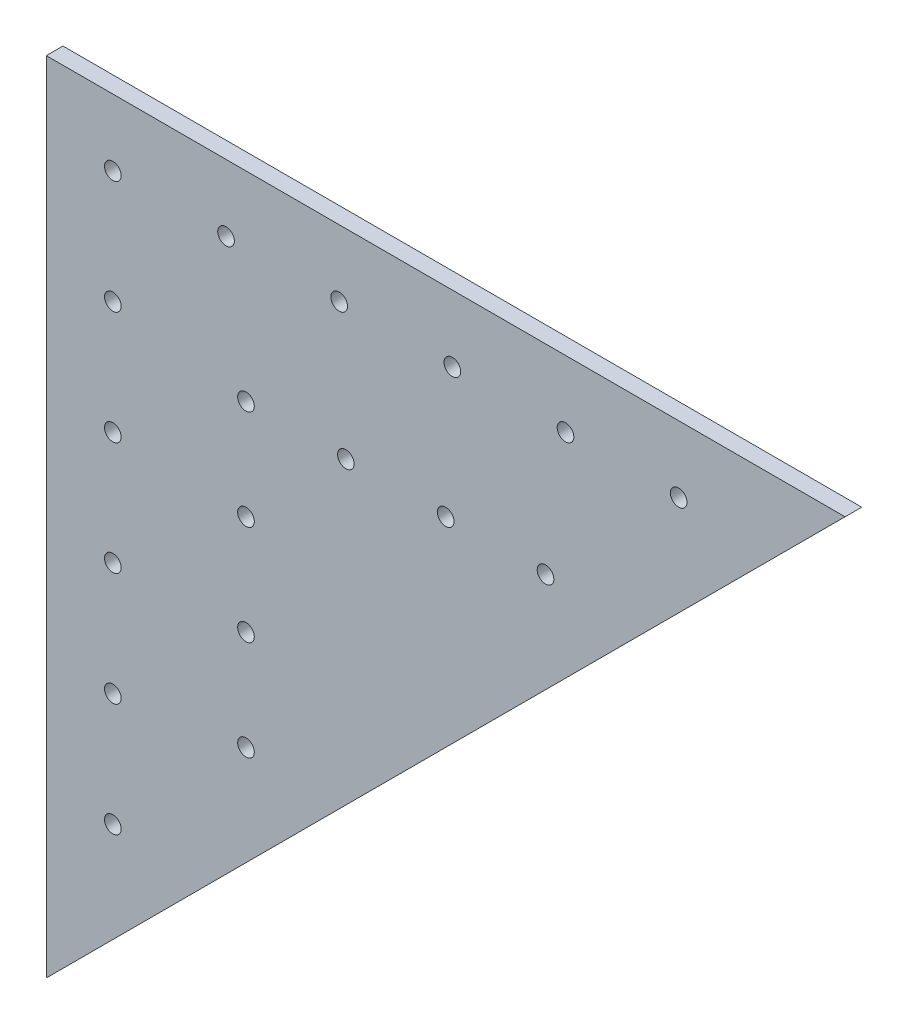
SolidWorks part; units mm, degrees
ref_plane "Front Plane" through (0, 0, 0) normal (0, 0, 1) x (1, 0, 0)
ref_plane "Top Plane" through (0, 0, 0) normal (0, 1, 0) x (1, 0, 0)
ref_plane "Right Plane" through (0, 0, 0) normal (1, 0, 0) x (0, 0, -1)
sketch "Sketch1" plane through (0, 0, 0) normal (0, 0, 1) x (1, 0, 0)
  line L0 (0, 0) -> (0, 152.4)
  line L1 (0, 152.4) -> (152.4, 152.4)
  line L2 (152.4, 152.4) -> (0, 0)
  dimension "D1" = 152.4
  dimension "D2" = 152.4
extrude "Boss-Extrude1" add sketch "Sketch1" along normal blind 3.175
sketch "Sketch2" plane through (0, 0, 3.175) normal (0, 0, 1) x (1, 0, 0)
  line L2 (50.8, 152.4) -> (50.8, 0)
  line L3 (50.8, 152.4) -> (50.8, 0) construction
  line L4 (152.4, 139.7) -> (12.7, 139.7)
  line L5 (12.7, 139.7) -> (12.7, 0)
  line L6 (152.4, 139.7) -> (12.7, 139.7) construction
  line L7 (12.7, 139.7) -> (12.7, 0) construction
  line L8 (152.4, 114.3) -> (38.1, 114.3) construction
  line L9 (38.1, 114.3) -> (38.1, 0) construction
  line L11 (152.4, 101.6) -> (0, 101.6)
  line L12 (50.8, 101.6) -> (50.8, 0) construction
  line L13 (152.4, 101.6) -> (50.8, 101.6) construction
  line L14 (152.4, 101.6) -> (38.1, 101.6) construction
  circle A0 centre (12.7, 139.7) radius 1.5875
  circle A1 centre (34.29, 139.7) radius 1.5875
  circle A2 centre (55.88, 139.7) radius 1.5875
  circle A3 centre (77.47, 139.7) radius 1.5875
  circle A4 centre (12.7, 118.11) radius 1.5875
  circle A5 centre (12.7, 96.52) radius 1.5875
  circle A6 centre (12.7, 74.93) radius 1.5875
  circle A7 centre (38.1, 114.3) radius 1.5875
  circle A8 centre (57.15, 114.3) radius 1.5875
  circle A9 centre (38.1, 95.25) radius 1.5875
  circle A10 centre (99.06, 139.7) radius 1.5875
  circle A11 centre (120.65, 139.7) radius 1.5875
  circle A12 centre (12.7, 53.34) radius 1.5875
  circle A13 centre (12.7, 31.75) radius 1.5875
  circle A14 centre (76.2, 114.3) radius 1.5875
  circle A15 centre (95.25, 114.3) radius 1.5875
  circle A16 centre (38.1, 76.2) radius 1.5875
  circle A17 centre (38.1, 57.15) radius 1.5875
  dimension "D3" = 3.175
  dimension "D6" = 3.175
  dimension "D1" = 12.7
  dimension "D2" = 12.7
  dimension "D9" = 50.8
  dimension "D10" = 50.8
  dimension "D4" = 6
  dimension "D5" = 6
  dimension "D7" = 4
  dimension "D8" = 4
extrude "r" cut sketch "Sketch2" against normal through all
